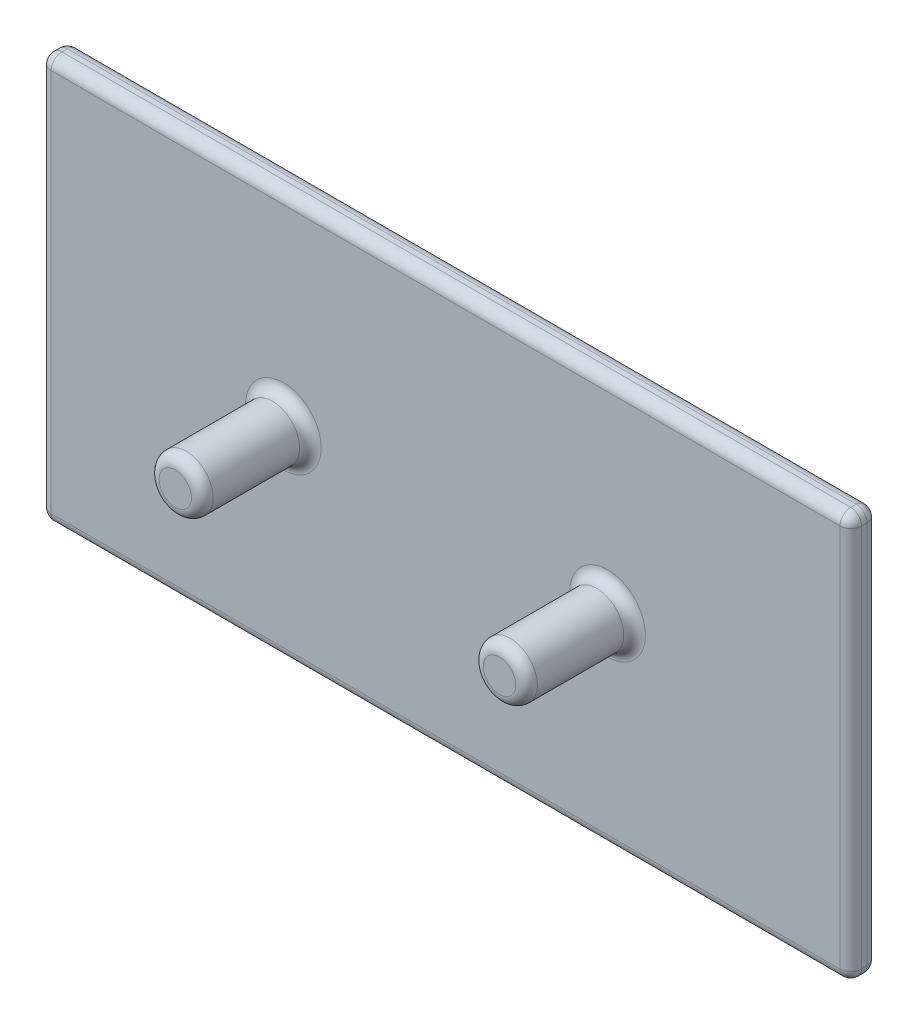
SolidWorks part; units mm, degrees
ref_plane "前基準面" through (0, 0, 0) normal (0, 0, 1) x (1, 0, 0)
ref_plane "上基準面" through (0, 0, 0) normal (0, 1, 0) x (1, 0, 0)
ref_plane "右基準面" through (0, 0, 0) normal (1, 0, 0) x (0, 0, -1)
sketch "草圖1" plane through (0, 0, 0) normal (0, 0, 1) x (1, 0, 0)
  line L1 (0, 0) -> (300, 0)
  line L2 (0, 0) -> (0, 150)
  line L3 (0, 150) -> (300, 150)
  line L4 (300, 0) -> (300, 150)
  dimension "D1" = 300
  dimension "D2" = 150
extrude "填料-伸長1" add sketch "草圖1" along normal blind 10
sketch "草圖2" plane through (0, 0, 10) normal (0, 0, 1) x (1, 0, 0)
  line L0 (150, 150) -> (150, -18.4939) construction
  line L1 (300, 150) -> (0, 150) construction
  line L2 (90, 75) -> (210, 75) construction
  line L3 (0, 0) -> (300, 0) construction
  circle A0 centre (90, 75) radius 10
  circle A1 centre (210, 75) radius 10
  dimension "D3" = 20
  dimension "D1" = 120
  dimension "D2" = 75
extrude "填料-伸長2" add sketch "草圖2" along normal blind 40
fillet "圓角1" radius 4 16 edges at (150, 0, 0) (150, 0, 10) (0, 75, 10) (80, 75, 10) (0, 75, 0) (300, 75, 0) (300, 75, 10) (150, 150, 10) (150, 150, 0) (0, 0, 5) (300, 0, 5) (300, 150, 5) (0, 150, 5) (200, 75, 10) (220, 75, 50) (100, 75, 50)
